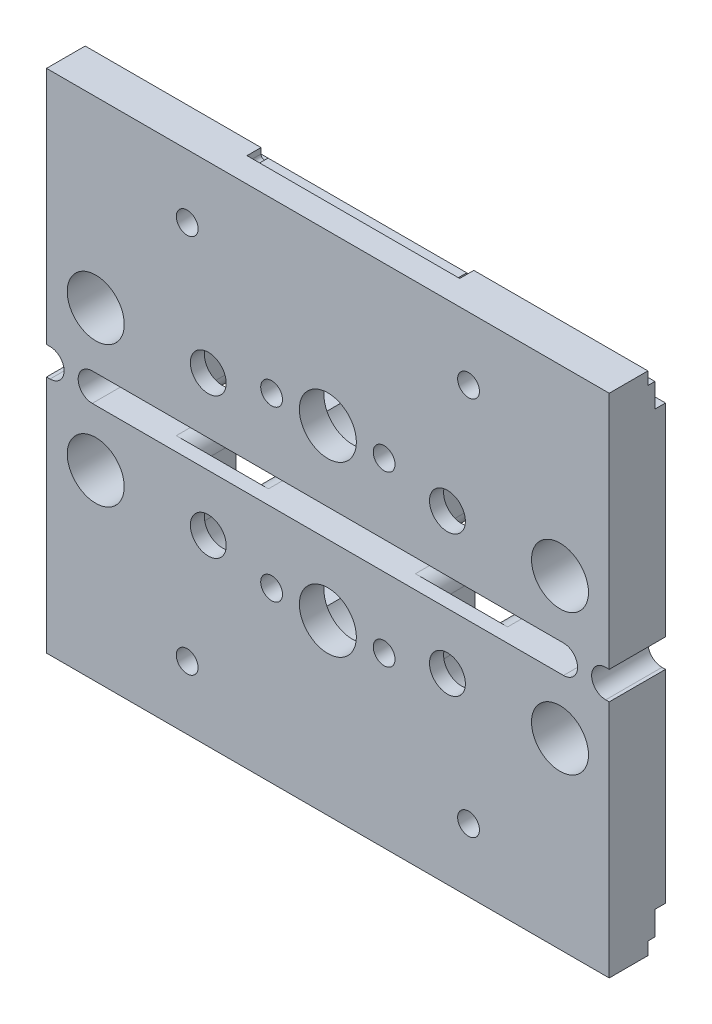
SolidWorks part; units mm, degrees
ref_plane "前视基准面" through (0, 0, 0) normal (0, 0, 1) x (1, 0, 0)
ref_plane "上视基准面" through (0, 0, 0) normal (0, 1, 0) x (1, 0, 0)
ref_plane "右视基准面" through (0, 0, 0) normal (1, 0, 0) x (0, 0, -1)
sketch "前视图草图" plane through (0, 0, 0) normal (0, 0, 1) x (1, 0, 0)
  line L0 (0, 0) -> (8.5179, 0) construction
  line L1 (0, 0) -> (0, 5.4227) construction
sketch "草图2" plane through (0, 0, 0) normal (0, 0, 1) x (1, 0, 0)
  line L0 (0, 0) -> (80, 0)
  line L1 (-200000, 0) -> (200008.5179, 0) construction
  line L2 (80, 0) -> (80, 34)
  line L3 (80, 34) -> (0, 34)
  line L4 (0, -200000) -> (0, 200005.4227) construction
  line L5 (0, 34) -> (0, 0)
  circle A0 centre (7, 8) radius 4.05
  circle A1 centre (40, 10) radius 4.05
  circle A2 centre (73, 8) radius 4.05
  dimension "D3" = 8
  dimension "D5" = 10
  dimension "D9" = 8.1
  dimension "D10" = 8.1
  dimension "D11" = 8.1
  dimension "D1" = 34
  dimension "D2" = 80
  dimension "D4" = 7
  dimension "D6" = 7
  dimension "D7" = 8
  dimension "D8" = 40
extrude "凸台-拉伸1" add sketch "草图2" along normal blind 8
sketch "草图3" plane through (0, 0, 8) normal (0, 0, 1) x (1, 0, 0)
  line L0 (16.088, 8) -> (31.4805, 8) construction
  line L1 (7, 8) -> (7, 16.8386) construction
  line L2 (73, 8) -> (73, 16.5917) construction
  line L4 (-200000, 0) -> (200008.5179, 0) construction
  circle A2 centre (23, 8) radius 2.55
  circle A3 centre (57, 8) radius 2.55
  dimension "D4" = 5.1
  dimension "D5" = 5.1
  dimension "D1" = 8
  dimension "D2" = 16
  dimension "D3" = 16
extrude "切除-拉伸1" cut sketch "草图3" against normal through all
sketch "草图4" plane through (80, 0, 0) normal (1, 0, 0) x (0, 0, -1)
  line L1 (0, -200000) -> (0, 200005.4227) construction
  line L2 (-1.5, 32.2) -> (-2.5, 32.2)
  line L3 (-2.5, 32.2) -> (-2.5, 34)
  line L4 (-8, 34) -> (0, 34) construction
  line L5 (-2.5, 34) -> (0, 34)
  line L6 (-1.5, 32.2) -> (-1.5, 28.8)
  line L7 (-1.5, 28.8) -> (0, 28.8)
  line L8 (0, 28.8) -> (0, 34)
  dimension "D1" = 3.4
  dimension "D2" = 2.5
  dimension "D3" = 1.5
  dimension "D4" = 1.8
extrude "切除-拉伸2" cut sketch "草图4" against normal through all
sketch "草图5" plane through (0, 0, 8) normal (0, 0, 1) x (1, 0, 0)
  line L0 (40, 10) -> (56.5376, 10) construction
  circle A0 centre (40, 10) radius 8 construction
  circle A1 centre (48, 10) radius 1.55
  circle A2 centre (32, 10) radius 1.55
  dimension "D1" = 3.1
  dimension "D2" = 3.1
  dimension "D3" = 16
extrude "切除-拉伸3" cut sketch "草图5" against normal through all
sketch "草图7" plane through (0, 0, 0) normal (0, 0, -1) x (-1, 0, 0)
  line L0 (-40, 12) -> (-40, -8.3696) construction
  line L1 (-23, 10) -> (-23, -2.3368) construction
  line L2 (200000, 0) -> (-200008.5179, 0) construction
  line L6 (-27.05, 10) -> (-27.05, 2.5)
  line L7 (-29.55, 0) -> (-16.45, 0)
  line L8 (-18.95, 2.5) -> (-18.95, 10)
  line L9 (-23, 8) -> (-23, 15.9045) construction
  line L13 (0, -200000) -> (0, 200005.4227) construction
  line L14 (-57, 8) -> (-57, 15.9045) construction
  line L15 (-57, 10) -> (-57, -2.3368) construction
  line L16 (-61.05, 2.5) -> (-61.05, 10)
  line L17 (-50.45, 0) -> (-63.55, 0)
  line L18 (-52.95, 10) -> (-52.95, 2.5)
  arc A1 (-18.95, 10) -> (-27.05, 10) centre (-23, 10) ccw
  arc A4 (-29.55, 0) -> (-27.05, 2.5) centre (-29.55, 2.5) ccw
  arc A5 (-18.95, 2.5) -> (-16.45, 0) centre (-16.45, 2.5) ccw
  arc A7 (-61.05, 2.5) -> (-63.55, 0) centre (-63.55, 2.5) cw
  arc A8 (-50.45, 0) -> (-52.95, 2.5) centre (-50.45, 2.5) cw
  arc A9 (-61.05, 10) -> (-52.95, 10) centre (-57, 10) cw
  dimension "D1" = 40
  dimension "D4" = 8.1
  dimension "D7" = 2.5
  dimension "D8" = 2.5
  dimension "D3" = 10
extrude "切除-拉伸4" cut sketch "草图7" against normal blind 6
sketch "草图8" plane through (0, 0, 0) normal (0, 0, -1) x (-1, 0, 0)
  line L0 (-40, 10) -> (-57.3165, 10) construction
  line L1 (-40, 20) -> (-40, 35.6562) construction
  line L2 (-30.5, 12.85) -> (-49.5, 12.85)
  line L3 (-49.5, 7.15) -> (-30.5, 7.15)
  line L4 (200000, 0) -> (-200008.5179, 0) construction
  arc A0 (-30.5, 7.15) -> (-30.5, 12.85) centre (-30.5, 10) ccw
  arc A1 (-49.5, 12.85) -> (-49.5, 7.15) centre (-49.5, 10) ccw
  dimension "D1" = 5.7
  dimension "D2" = 9.5
  dimension "D3" = 9.5
  dimension "D4" = 10
extrude "切除-拉伸5" cut sketch "草图8" against normal blind 4.5
sketch "草图20" plane through (0, 0, 0) normal (0, 0, -1) x (-1, 0, 0)
  circle A0 centre (-40, 10) radius 5.5
  dimension "D1" = 11
extrude "切除-拉伸12" cut sketch "草图20" against normal blind 4.5
sketch "草图25" plane through (0, 0, 0) normal (0, 0, -1) x (-1, 0, 0)
  line L0 (-49.0646, 25) -> (-33.429, 25) construction
  line L1 (-60, 37.1874) -> (-60, 21.6501) construction
  line L2 (-20, 37.1874) -> (-20, 20.6667) construction
  line L3 (0, 34) -> (-80, 34) construction
  line L4 (-80, 0) -> (-80, 28.8) construction
  line L5 (0, -200000) -> (0, 200005.4227) construction
  circle A0 centre (-60, 25) radius 1.55
  circle A1 centre (-20, 25) radius 1.55
  dimension "D4" = 3.1
  dimension "D5" = 3.1
  dimension "D1" = 9
  dimension "D2" = 20
  dimension "D3" = 20
extrude "切除-拉伸13" cut sketch "草图25" against normal through all
sketch "草图19" plane through (0, 0, 2.5) normal (0, 0, -1) x (-1, 0, 0)
  line L0 (0, 34) -> (-80, 34) construction
  line L1 (-25, 34) -> (-55.2479, 34)
  line L2 (-25, 34) -> (-25, 33.2)
  line L3 (-26, 33.2) -> (-54.2479, 33.2)
  line L4 (-55.2479, 34) -> (-55.2479, 33.2)
  line L5 (0, -200000) -> (0, 200005.4227) construction
  line L7 (0, 32.2) -> (-80, 32.2) construction
  line L8 (-56.3335, 32.7) -> (-52.9089, 32.7) construction
  line L9 (-55.2479, 1028.5823) -> (-55.2479, 33.2) construction
  line L10 (-25, 1028.5823) -> (-25, 32.7) construction
  line L11 (-55.2479, 32.7) -> (-55.2479, -973.3) construction
  line L12 (-25, 32.7) -> (-25, -973.3) construction
  arc A3 (-55.2479, 33.2) -> (-54.2479, 33.2) centre (-54.7479, 33.2) ccw
  arc A6 (-26, 33.2) -> (-25, 33.2) centre (-25.5, 33.2) ccw
  dimension "D3" = 1
  dimension "D4" = 1
  dimension "D2" = 0.8
  dimension "D1" = 0.5
  dimension "D9" = 25
extrude "切除-拉伸11" cut sketch "草图19" against normal blind 2
sketch "草图22" plane through (0, 0, 8) normal (0, 0, 1) x (1, 0, 0)
  line L1 (0, -200000) -> (0, 200005.4227) construction
  line L2 (0.5, -4) -> (6.5, -4)
  line L4 (79.5, 0) -> (73.5, 0)
  line L5 (4.5, 1.9875) -> (4.5, -4.1402) construction
  line L6 (75.5, -11.5647) -> (75.5, -5.1636) construction
  line L7 (80, 0) -> (80, 34) construction
  line L8 (73.5, -4) -> (79.5, -4)
  line L9 (6.5, 0) -> (0.5, 0)
  line L10 (77.5, -2.9635) -> (77.5, -4.3032) construction
  line L11 (2.5, -8.393) -> (2.5, -15.1693) construction
  arc A0 (6.5, 0) -> (6.5, -4) centre (6.5, -2) ccw
  arc A1 (73.5, -4) -> (73.5, 0) centre (73.5, -2) ccw
  arc A2 (0.5, -4) -> (0.5, 0) centre (0.5, -2) ccw
  arc A3 (79.5, 0) -> (79.5, -4) centre (79.5, -2) ccw
  dimension "D1" = 4.5
  dimension "D2" = 4.5
  dimension "D3" = 4
  dimension "D4" = 2.5
  dimension "D5" = 2.5
extrude "凸台-拉伸2" add sketch "草图22" against normal blind 8
ref_plane "基准面1" through (0, -2, 0) normal (0, -1, 0) x (-1, 0, 0)
mirror "镜向2" about plane through (0, -2, 0) normal (0, -1, 0) of "切除-拉伸13", "切除-拉伸11", "切除-拉伸12", "切除-拉伸5", "切除-拉伸4", "切除-拉伸2", "切除-拉伸1", "凸台-拉伸1", "切除-拉伸3"
sketch "草图23" plane through (0, 0, 0) normal (0, 0, -1) x (-1, 0, 0)
  line L0 (-80, 0) -> (0, 0)
  line L1 (0, 0) -> (0, -4)
  line L2 (0, -4) -> (-80, -4)
  line L3 (-80, -4) -> (-80, 0)
sketch "草图24" plane through (0, 0, 8) normal (0, 0, 1) x (1, 0, 0)
  line L0 (80, -4) -> (80, 0)
  line L1 (80, 0) -> (0, 0)
  line L2 (0, 0) -> (0, -4)
  line L3 (0, -4) -> (80, -4)
